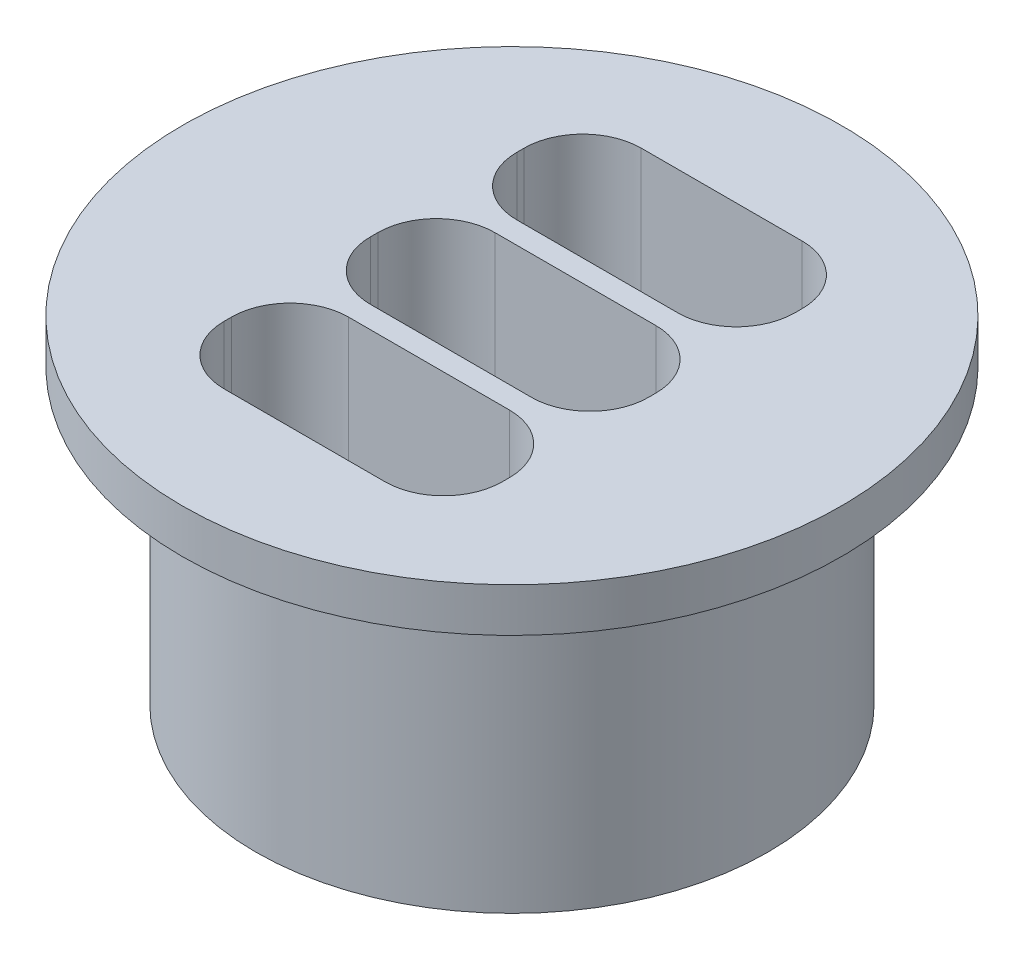
SolidWorks part; units mm, degrees
ref_plane "Front Plane" through (0, 0, 0) normal (0, 0, 1) x (1, 0, 0)
ref_plane "Top Plane" through (0, 0, 0) normal (0, 1, 0) x (1, 0, 0)
ref_plane "Right Plane" through (0, 0, 0) normal (1, 0, 0) x (0, 0, -1)
sketch "Sketch1" plane through (0, 0, 0) normal (0, 1, 0) x (1, 0, 0)
  circle A0 centre (0, 0) radius 17.5
  dimension "D1" = 35
extrude "Boss-Extrude1" add sketch "Sketch1" along normal blind 20
sketch "Sketch2" plane through (0, 20, 0) normal (0, 1, 0) x (1, 0, 0)
  circle A0 centre (0, 0) radius 21.5
  dimension "D1" = 43
extrude "Boss-Extrude2" add sketch "Sketch2" along normal blind 3
sketch "Sketch3" plane through (0, 23, 0) normal (0, 1, 0) x (1, 0, 0)
  line L0 (0, 16.1651) -> (0, -18.7714) construction
  line L1 (-9.5, 4.3338) -> (-9.5, -4.1662)
  line L2 (-9.5, 14.3338) -> (9.5, 14.3338)
  line L3 (-9.5, 14.3338) -> (-9.5, 5.8338)
  line L4 (-9.5, 5.8338) -> (9.5, 5.8338)
  line L5 (9.5, 14.3338) -> (9.5, 5.8338)
  line L6 (-9.5, 14.3338) -> (9.5, 5.8338) construction
  line L7 (-9.5, 5.8338) -> (9.5, 14.3338) construction
  line L8 (-9.5, 4.3338) -> (9.5, 4.3338)
  line L9 (9.5, 4.3338) -> (9.5, -4.1662)
  line L10 (-9.5, -4.1662) -> (9.5, -4.1662)
  line L11 (-9.5, -5.6662) -> (-9.5, -14.1662)
  line L12 (-9.5, -5.6662) -> (9.5, -5.6662)
  line L13 (9.5, -5.6662) -> (9.5, -14.1662)
  line L14 (-9.5, -14.1662) -> (9.5, -14.1662)
  point P3 (0, 10.0838)
  dimension "D1" = 19
  dimension "D2" = 8.5
  dimension "D3" = 3
extrude "Cut-Extrude3" cut sketch "Sketch3" against normal blind 23
fillet "Fillet11" radius 4 8 edges at (9.5, 11.5, 5.6662) (-9.5, 11.5, 14.1662) (-9.5, 11.5, 5.6662) (9.5, 11.5, 14.1662) (9.5, 11.5, 4.1662) (-9.5, 11.5, 4.1662) (-9.5, 11.5, -4.3338) (9.5, 11.5, -4.3338)
fillet "Fillet12" radius 4 4 edges at (-9.5, 11.5, -14.3338) (9.5, 11.5, -5.8338) (-9.5, 11.5, -5.8338) (9.5, 11.5, -14.3338)
sketch "Sketch6" plane through (0, 23, 0) normal (0, 1, 0) x (1, 0, 0)
  circle A0 centre (0, 0) radius 21.5
  circle A1 centre (0, 0) radius 22.5208
extrude "Boss-Extrude4" add sketch "Sketch6" against normal blind 3
